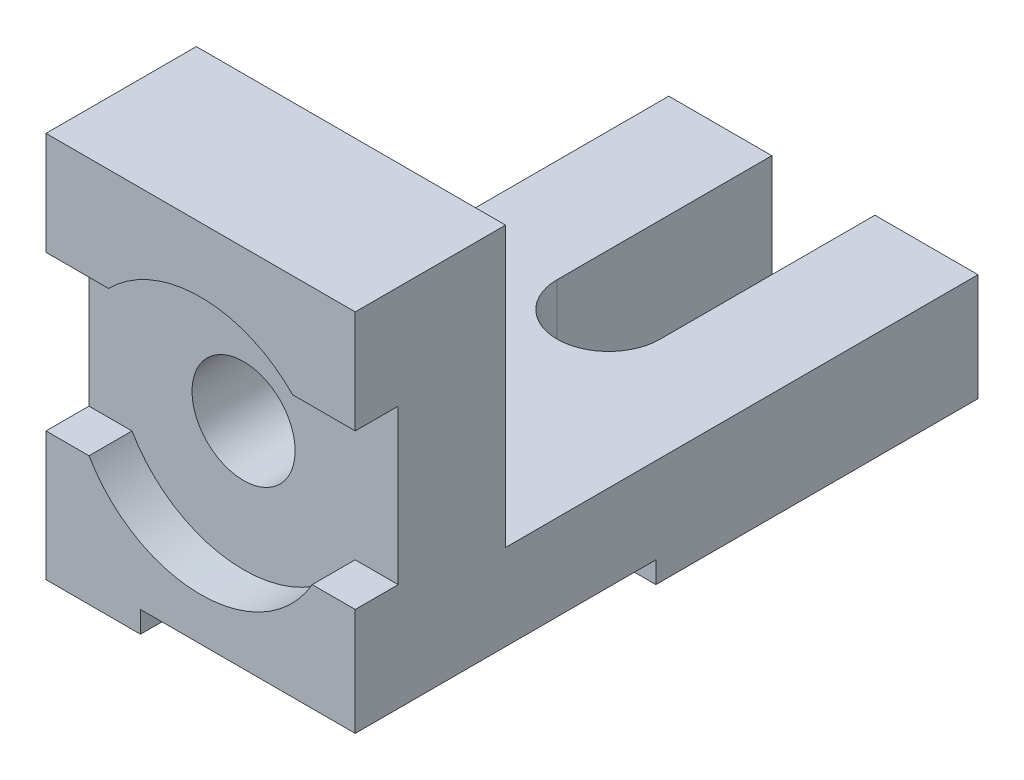
SolidWorks part; units mm, degrees
ref_plane "Front Plane" through (0, 0, 0) normal (0, 0, 1) x (1, 0, 0)
ref_plane "Top Plane" through (0, 0, 0) normal (0, 1, 0) x (1, 0, 0)
ref_plane "Right Plane" through (0, 0, 0) normal (1, 0, 0) x (0, 0, -1)
sketch "Sketch1" plane through (0, 0, 0) normal (1, 0, 0) x (0, 0, -1)
  line L11 (0, 0) -> (145, 0)
  line L12 (145, 0) -> (145, 25)
  line L13 (145, 25) -> (35, 25)
  line L14 (35, 25) -> (35, 90)
  line L15 (35, 90) -> (0, 90)
  line L16 (0, 90) -> (0, 66)
  line L17 (0, 66) -> (10, 66)
  line L18 (10, 66) -> (10, 30)
  line L19 (10, 30) -> (0, 30)
  line L20 (0, 30) -> (0, 0)
  dimension "D1" = 145
  dimension "D2" = 25
  dimension "D3" = 35
  dimension "D4" = 24
  dimension "D5" = 10
  dimension "D6" = 30
  dimension "D7" = 90
extrude "Boss-Extrude1" add sketch "Sketch1" against normal blind 72
sketch "Sketch2" plane through (0, 25, 0) normal (0, 1, 0) x (1, 0, 0)
  line L0 (-24, 145) -> (-24, 95)
  line L1 (-72, 145) -> (0, 145) construction
  line L2 (-48, 145) -> (-48, 95)
  line L3 (-36, 145) -> (-36, 95) construction
  arc A0 (-48, 95) -> (-24, 95) centre (-36, 95) ccw
  point P8 (-36, 104.2027)
  dimension "D2" = 50
  dimension "D1" = 24
extrude "Cut-Extrude1" cut sketch "Sketch2" against normal blind 25 and the other way through all
ref_plane "Plane1" through (0, 0, 0) normal (0, 0, -1) x (-1, 0, 0)
sketch "Sketch3" plane through (0, 0, 0) normal (0, 0, -1) x (-1, 0, 0)
  line L0 (72, 0) -> (0, 0) construction
  line L1 (0, 90) -> (0, 66) construction
  circle A0 centre (36, 45) radius 30
  point P6 (-10.7991, 34.1124)
  dimension "D3" = 60
  dimension "D1" = 45
  dimension "D2" = 36
extrude "Cut-Extrude2" cut sketch "Sketch3" along normal up to surface (10 mm away) up to face at (-36, 48, -10)
ref_plane "Plane2" through (0, 0, -10) normal (0, 0, 1) x (1, 0, 0)
sketch "Sketch4" plane through (0, 0, -10) normal (0, 0, 1) x (1, 0, 0)
  line L0 (-72, 0) -> (0, 0) construction
  line L2 (0, 66) -> (0, 30) construction
  circle A0 centre (-36, 45) radius 12
  point P6 (0, 47.7521)
  dimension "D3" = 24
  dimension "D1" = 45
  dimension "D2" = 36
extrude "Cut-Extrude3" cut sketch "Sketch4" against normal up to surface (25 mm away) up to face at (-36, 57.5, -35)
ref_plane "Plane3" through (0, 0, 0) normal (0, 0, 1) x (1, 0, 0)
sketch "Sketch5" plane through (0, 0, 0) normal (0, 0, 1) x (1, 0, 0)
  line L0 (0, 5) -> (-50, 5)
  line L1 (0, 30) -> (0, 0) construction
  line L2 (-50, 5) -> (-50, 0)
  line L3 (-72, 0) -> (0, 0) construction
  line L4 (-50, 0) -> (0, 0)
  line L5 (0, 0) -> (0, 5)
  dimension "D1" = 50
  dimension "D2" = 5
extrude "Cut-Extrude4" cut sketch "Sketch5" against normal blind 70
